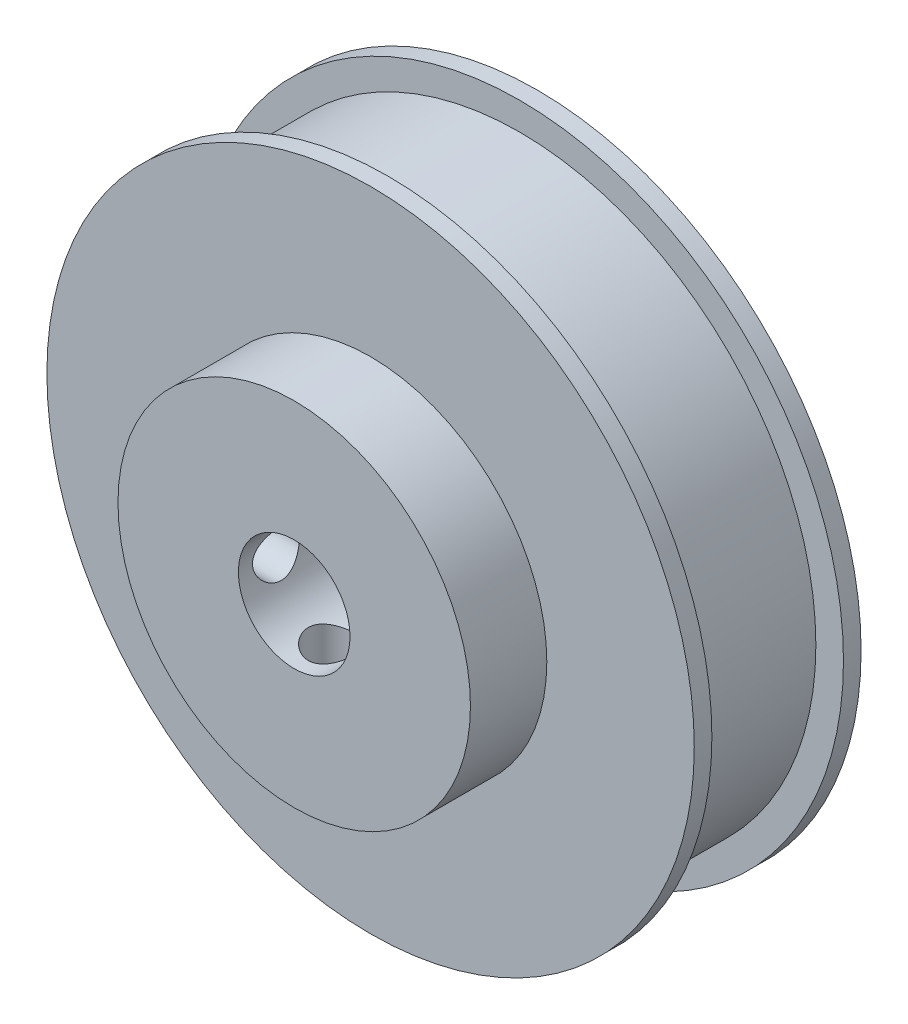
SolidWorks part; units mm, degrees
ref_plane "Alzado" through (0, 0, 0) normal (0, 0, 1) x (1, 0, 0)
ref_plane "Planta" through (0, 0, 0) normal (0, 1, 0) x (1, 0, 0)
ref_plane "Vista lateral" through (0, 0, 0) normal (1, 0, 0) x (0, 0, -1)
sketch "Croquis1" plane through (0, 0, 0) normal (0, 0, 1) x (1, 0, 0)
  circle A0 centre (0, 0) radius 27.55
  dimension "D1" = 55.1
extrude "Saliente-Extruir1" add sketch "Croquis1" along normal blind 1.5
sketch "Croquis2" plane through (0, 0, 1.5) normal (0, 0, 1) x (1, 0, 0)
  circle A0 centre (0, 0) radius 25.2
  dimension "D1" = 50.4
extrude "Saliente-Extruir2" add sketch "Croquis2" along normal blind 11.2
sketch "Croquis3" plane through (0, 0, 12.7) normal (0, 0, 1) x (1, 0, 0)
  circle A0 centre (0, 0) radius 27.55
  dimension "D1" = 55.1
extrude "Saliente-Extruir3" add sketch "Croquis3" along normal blind 1.5
sketch "Croquis8" plane through (0, 0, 14.2) normal (0, 0, 1) x (1, 0, 0)
  circle A0 centre (0, 0) radius 15
  dimension "D1" = 30
extrude "Saliente-Extruir5" add sketch "Croquis8" along normal blind 6.5
sketch "Croquis6" plane through (0, 0, 0) normal (0, 1, 0) x (1, 0, 0)
  line L0 (0, 0) -> (0, -17.5) construction
  circle A0 centre (0, -17.5) radius 2
  dimension "D2" = 4
  dimension "D1" = 17.5
extrude "Cortar-Extruir3" cut sketch "Croquis6" against normal through all
sketch "Croquis5" plane through (0, 0, 0) normal (1, 0, 0) x (0, 0, -1)
  line L0 (0, 0) -> (-17.5, 0) construction
  circle A0 centre (-17.5, 0) radius 2
  dimension "D2" = 4
  dimension "D1" = 17.5
extrude "Cortar-Extruir2" cut sketch "Croquis5" against normal through all
sketch "Croquis4" plane through (0, 0, 20.7) normal (0, 0, 1) x (1, 0, 0)
  circle A0 centre (0, 0) radius 4.75
  dimension "D1" = 9.5
extrude "Cortar-Extruir1" cut sketch "Croquis4" against normal through all
